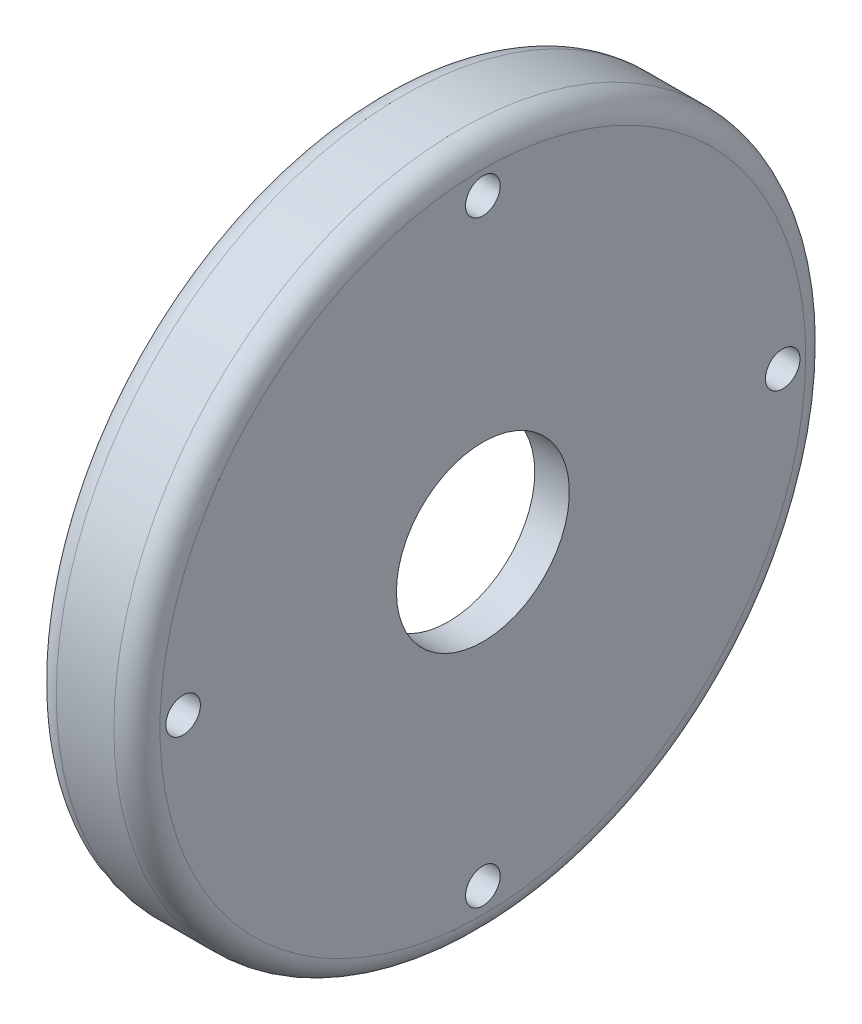
SolidWorks part; units mm, degrees
ref_plane "Plane1" through (0, 0, 0) normal (0, 0, 1) x (1, 0, 0)
ref_plane "Plane2" through (0, 0, 0) normal (0, 1, 0) x (1, 0, 0)
ref_plane "Plane3" through (0, 0, 0) normal (1, 0, 0) x (0, 0, -1)
other "Configuration Table"
sketch "HoldingSke" plane through (0, 0, 0) normal (0, 1, 0) x (1, 0, 0)
  line L0 (0, 0) -> (0.7431, -0.6691)
  line L1 (-15, 0) -> (100, 0) construction
  line L2 (0, 0) -> (-2.1039, 2.3779)
  line L3 (0, 0) -> (-11.863, 4.5341)
  line L4 (0, 0) -> (6.4178, 5.7786)
  line L5 (0, 0) -> (-23.7986, -8.8762)
  line L6 (0, 0) -> (-10.5278, -7.1032)
  line L7 (-2.1039, 2.3779) -> (3.3635, 27.1825)
  line L8 (-76.2, 3.3779) -> (-54.61, 3.3779)
  line L9 (-71.009, 38.7566) -> (-53.1078, 45.2721)
  line L10 (-76.2, 71.12) -> (104.1128, 71.12)
  line L11 (0, 0) -> (-6, 0)
  line L12 (-76.2, 101.6) -> (-76.162, 101.6)
  line L13 (24.9733, 27.94) -> (52.9518, 28.4284)
  line L14 (24.9733, 27.94) -> (24.9743, 27.94)
  line L15 (24.9733, 27.94) -> (100.4006, 29.5858)
  circle A0 centre (0, 0) radius 30
  circle A1 centre (0, 0) radius 12.7
  circle A2 centre (0, 0) radius 12.7
  dimension "MHD" = 25.4
  dimension "Hub_dia" = 25.4
  dimension "Diameter" = 60
  dimension "Num_teeth" = 42
  dimension "Pitch" = 1
  dimension "Overall_len" = 25.4
  dimension "Show_teeth" = 42
  dimension "Thickness" = 12.7
  dimension "OAL" = 25.4001
  dimension "T_dim" = 21.59
  dimension "Ap" = 20
  dimension "H" = 19.05
  dimension "Pitch_radius" = 180.3128
  dimension "Width" = 6
  dimension "Backlash" = 0.038
  dimension "Addendum_fac" = 1
  dimension "Dedendum_fac" = 1.25
  dimension "Clearance_fac" = 0.25
  dimension "Dedendum_add" = 0.001
  dimension "Module" = 1
sketch "BasProSke" plane through (0, 0, 0) normal (0, 1, 0) x (1, 0, 0)
  line L0 (-10, 0) -> (60, 0) construction
  line L1 (0, 20) -> (0, 30)
  line L2 (0, 20) -> (6, 20)
  line L3 (6, 20) -> (6, 30)
  line L4 (6, 30) -> (0, 30)
  dimension "Diameter" = 60
  dimension "Thickness" = 6
  dimension "Inside_diameter" = 40
revolve "Base-Revolve" add sketch "BasProSke" angle 360 about L0
sketch "TooCutSke" plane through (0, 0, 0) normal (1, 0, 0) x (0, 0, -1)
  line L3 (0.8802, 20.9815) -> (0.8802, 53.6633) construction
  line L4 (0, 0) -> (0, 59.563) construction
  line L5 (0, 0) -> (-5.1061, 68.1364) construction
  line L6 (-8.8932, 17.1435) -> (36.4098, 20.5385) construction
  circle A0 centre (0, 0) radius 21 construction
  circle A1 centre (0, 0) radius 22.251 construction
  circle A2 centre (0, 0) radius 17.7602 construction
  circle A3 centre (0, 0) radius 19.9746 construction
  arc A4 (1.2284, 19.9368) -> (0.2819, 22.2492) centre (-8.8932, 17.1435) ccw
  arc A5 (1.2284, 19.9368) -> (-1.2284, 19.9368) centre (0, 0) ccw
  arc A6 (0.2819, 22.2492) -> (-0.2819, 22.2492) centre (0, 0) ccw
  arc A7 (-0.2819, 22.2492) -> (-1.2284, 19.9368) centre (8.8932, 17.1435) ccw
  dimension "Pitch_dia" = 42
  dimension "Base_dia" = 35.5204
  dimension "Root_dia" = 44.502
  dimension "Overcut_dia" = 39.9492
  dimension "Flank_rad" = 10.5
  dimension "Half_ang" = 4.286
  dimension "Half_CT" = 0.8802
extrude "ToothCut" cut sketch "TooCutSke" along normal through all
fillet "Breaks" [suppressed] radius 0.1
fillet "RootFillets" [suppressed] radius 0.251
pattern_circular "TeethCuts" count 42 every 8.571 about axis through (-10, 0, 0) along (1, 0, 0) of "RootFillets", "Breaks", "ToothCut"
sketch "Sketch1" plane through (6, 0, 0) normal (1, 0, 0) x (0, 0, -1)
  circle A0 centre (0, 0) radius 30 construction
  circle A1 centre (0, 0) radius 30
extrude "Boss-Extrude1" add sketch "Sketch1" along normal blind 3
sketch "Sketch2" plane through (0, 0, 0) normal (-1, 0, 0) x (0, 0, 1)
  circle A0 centre (0, 26) radius 1.5
  circle A1 centre (26, 0) radius 1.5
  circle A2 centre (-26, 0) radius 1.5
  circle A3 centre (0, -25.8269) radius 1.5
  circle A4 centre (0, 0) radius 26 construction
  circle A5 centre (0, 0) radius 7.5
  dimension "D1" = 52
  dimension "D2" = 3
  dimension "D3" = 15
extrude "Cut-Extrude2" cut sketch "Sketch2" against normal through all
fillet "Fillet1" radius 2 2 edges at (9, 0, -30) (0, 0, 30)
equation "' \"Module@HoldingSke\" = 6.35"
equation "' \"Num_teeth@HoldingSke\" = 24"
equation "' \"Ap@HoldingSke\" =  14.5"
equation "' \"Ap@HoldingSke\" = 14.5"
equation "' \"Width@HoldingSke\" = 12"
equation "' \"Diameter@HoldingSke\" = 8 * 25.4"
equation "' \"Show_teeth@HoldingSke\" = 100"
equation "' \"Backlash@HoldingSke\" = 0.009 * 25.4"
equation "' \"Addendum_fac@HoldingSke\" = 1.0"
equation "' \"Dedendum_fac@HoldingSke\" = 1.25"
equation "' \"Dedendum_add@HoldingSke\" = 0.00005 * 25.4"
equation "' \"Clearance_fac@HoldingSke\" = 0.25"
equation "\"Pitch@HoldingSke\" = 1 / \"Module@HoldingSke\" "
equation "\"Overcut_dia@TooCutSke\" = (\"Num_teeth@HoldingSke\" - 2 * \"Addendum_fac@HoldingSke\") / \"Pitch@HoldingSke\" - 0.002 * 25.4"
equation "\"Pitch_dia@TooCutSke\" = \"Num_teeth@HoldingSke\" / \"Pitch@HoldingSke\""
equation "\"Base_dia@TooCutSke\" = \"Num_teeth@HoldingSke\" / \"Pitch@HoldingSke\" * cos((\"Ap@HoldingSke\"  * 3.14159265 / 180)) * 0.90"
equation "\"Root_dia@TooCutSke\" = \"Num_teeth@HoldingSke\"  / \"Pitch@HoldingSke\" + 2 *  \"Dedendum_fac@HoldingSke\"/ \"Pitch@HoldingSke\" + \"Dedendum_add@HoldingSke\" * 2"
equation "\"Half_ang@TooCutSke\" = 180 / \"Num_teeth@HoldingSke\""
equation "\"Half_CT@TooCutSke\" = \"Num_teeth@HoldingSke\" / \"Pitch@HoldingSke\" * sin((3.14159265 / 2 / \"Num_teeth@HoldingSke\")) / 2 + 10 * \"Backlash@HoldingSke\" / 4"
equation "\"Flank_rad@TooCutSke\" = \"Num_teeth@HoldingSke\" / \"Pitch@HoldingSke\" / 4"
equation "\"Radius@RootFillets\"= \"Clearance_fac@HoldingSke\" / \"Pitch@HoldingSke\" + \"Dedendum_add@HoldingSke\""
equation "\"Break_rad@Breaks\" = 0.02 / \"Pitch@HoldingSke\" * 5"
equation "\"Num_teeth@TeethCuts\" = int( \"Show_teeth@HoldingSke\" ) + 1"
equation "\"Num_teeth@TeethCuts\" = ((sgn( \"Num_teeth@TeethCuts\" - \"Num_teeth@HoldingSke\" )-1)*( \"Num_teeth@TeethCuts\" - \"Num_teeth@HoldingSke\" ))/-2+ \"Num_teeth@HoldingSke\""
equation "\"Num_teeth@TeethCuts\" = ((sgn( \"Num_teeth@TeethCuts\" - 2.0)+1)*( \"Num_teeth@TeethCuts\" - 2.0))/2 +2.0"
equation "\"Angle@TeethCuts\" = 360.0 / \"Num_teeth@HoldingSke\""
equation "\"Diameter@BasProSke\" = \"Num_teeth@HoldingSke\"  / \"Pitch@HoldingSke\" + 2 *  \"Dedendum_fac@HoldingSke\"/ \"Pitch@HoldingSke\" + \"Dedendum_add@HoldingSke\" * 2 + 0.002 * 25.4"
equation "\"Diameter@BasProSke\" = ((sgn( \"Diameter@BasProSke\"  - \"Diameter@HoldingSke\" )+1)*( \"Diameter@BasProSke\"  - \"Diameter@HoldingSke\" ))/2 + \"Diameter@HoldingSke\""
equation "\"Inside_diameter@BasProSke\" =  (\"Num_teeth@HoldingSke\" - 2 * \"Addendum_fac@HoldingSke\") / \"Pitch@HoldingSke\" "
equation "\"Thickness@BasProSke\"  = \"Width@HoldingSke\""
